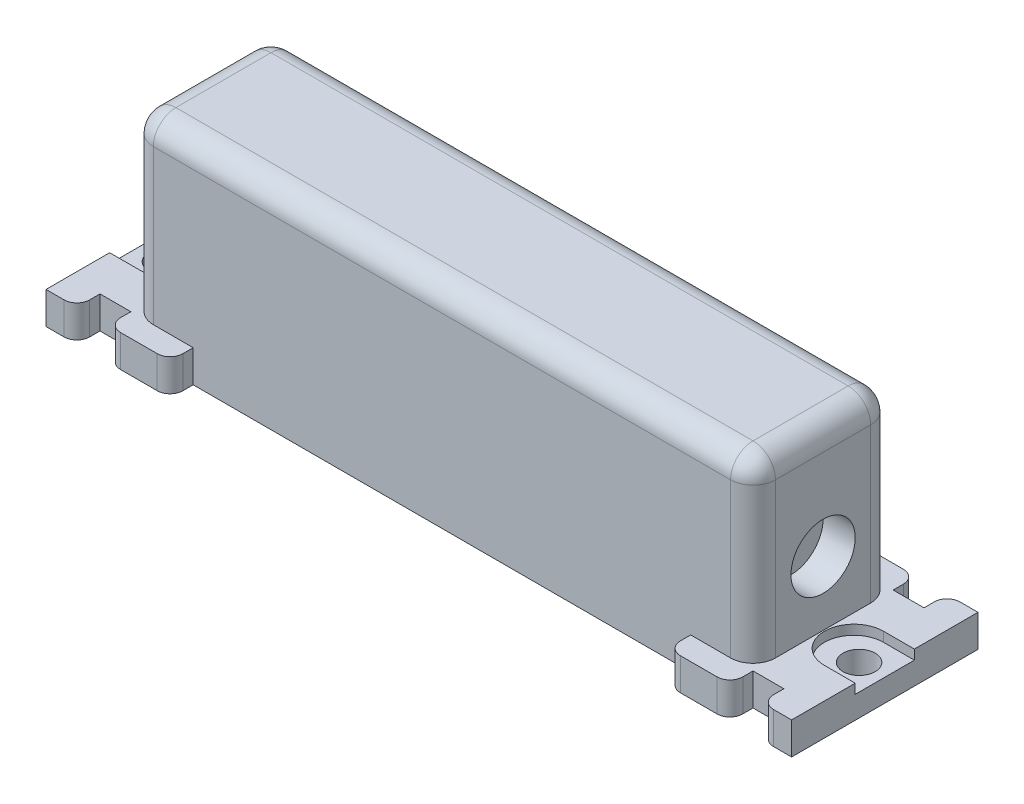
SolidWorks part; units mm, degrees
ref_plane "正面" through (0, 0, 0) normal (0, 0, 1) x (1, 0, 0)
ref_plane "平面" through (0, 0, 0) normal (0, 1, 0) x (1, 0, 0)
ref_plane "右側面" through (0, 0, 0) normal (1, 0, 0) x (0, 0, -1)
sketch "ｽｹｯﾁ1" plane through (0, 0, 0) normal (0, 1, 0) x (1, 0, 0)
  line L0 (-58, -14.5) -> (-58, 14.5)
  line L1 (-58, 14.5) -> (-55.2, 14.5)
  line L2 (-53.2, 12.5) -> (-53.2, 10.9)
  line L3 (-53.2, 10.9) -> (-48.4, 10.9)
  line L4 (-48.4, 10.9) -> (-48.4, 12.5)
  line L5 (57.2676, 0) -> (-76.0537, 0) construction
  line L6 (0, 42.7127) -> (0, -43.6312) construction
  line L7 (-46.4, 14.5) -> (-40.7, 14.5)
  line L8 (-38.7, 12.5) -> (-38.7, 10.9)
  line L9 (-38.7, 10.9) -> (38.7, 10.9)
  line L10 (58, -14.5) -> (58, 14.5)
  line L11 (38.7, 12.5) -> (38.7, 10.9)
  line L12 (46.4, 14.5) -> (40.7, 14.5)
  line L13 (48.4, 10.9) -> (48.4, 12.5)
  line L14 (53.2, 10.9) -> (48.4, 10.9)
  line L15 (53.2, 12.5) -> (53.2, 10.9)
  line L16 (58, 14.5) -> (55.2, 14.5)
  line L17 (58, -14.5) -> (55.2, -14.5)
  line L18 (53.2, -12.5) -> (53.2, -10.9)
  line L19 (53.2, -10.9) -> (48.4, -10.9)
  line L20 (48.4, -10.9) -> (48.4, -12.5)
  line L21 (46.4, -14.5) -> (40.7, -14.5)
  line L22 (38.7, -12.5) -> (38.7, -10.9)
  line L23 (-38.7, -10.9) -> (38.7, -10.9)
  line L24 (-38.7, -12.5) -> (-38.7, -10.9)
  line L25 (-46.4, -14.5) -> (-40.7, -14.5)
  line L26 (-48.4, -10.9) -> (-48.4, -12.5)
  line L27 (-53.2, -10.9) -> (-48.4, -10.9)
  line L28 (-53.2, -12.5) -> (-53.2, -10.9)
  line L29 (-58, -14.5) -> (-55.2, -14.5)
  arc A0 (-55.2, 14.5) -> (-53.2, 12.5) centre (-55.2, 12.5) cw
  arc A1 (-48.4, 12.5) -> (-46.4, 14.5) centre (-46.4, 12.5) cw
  arc A2 (-40.7, 14.5) -> (-38.7, 12.5) centre (-40.7, 12.5) cw
  arc A3 (40.7, 14.5) -> (38.7, 12.5) centre (40.7, 12.5) ccw
  arc A4 (48.4, 12.5) -> (46.4, 14.5) centre (46.4, 12.5) ccw
  arc A5 (55.2, 14.5) -> (53.2, 12.5) centre (55.2, 12.5) ccw
  arc A6 (55.2, -14.5) -> (53.2, -12.5) centre (55.2, -12.5) cw
  arc A7 (48.4, -12.5) -> (46.4, -14.5) centre (46.4, -12.5) cw
  arc A8 (40.7, -14.5) -> (38.7, -12.5) centre (40.7, -12.5) cw
  arc A9 (-40.7, -14.5) -> (-38.7, -12.5) centre (-40.7, -12.5) ccw
  arc A10 (-48.4, -12.5) -> (-46.4, -14.5) centre (-46.4, -12.5) ccw
  arc A11 (-55.2, -14.5) -> (-53.2, -12.5) centre (-55.2, -12.5) ccw
  point P11 (-50.8, 10.9)
  point P25 (0, 10.9)
  point P37 (-58, 0)
  point P62 (0, -10.9)
  point P63 (58, 0)
  dimension "D4" = 9.6
  dimension "D7" = 2
  dimension "D8" = 2
  dimension "D9" = 2
  dimension "D1" = 14.5
  dimension "D2" = 58
  dimension "D3" = 19.3
  dimension "D5" = 4.8
  dimension "D6" = 3.6
extrude "ﾎﾞｽ - 押し出し2" add sketch "ｽｹｯﾁ1" along normal blind 5 contours L9 L11 A3 L12 A4 L13 L14 L15 A5 L16 L10 L17 A6 L18 L19 L20 A7 L21 A8 L22 L23 L24 A9 L25 A10 L26 L27 L28 A11 L29 L0 L1 A0 L2 L3 L4 A1 L7 A2 L8
sketch "ｽｹｯﾁ3" plane through (0, 5, 0) normal (0, 1, 0) x (1, 0, 0)
  line L0 (-38.7, 10.9) -> (38.7, 10.9) construction
  line L1 (-44.9, 10.9) -> (44.9, 10.9)
  line L2 (-48.4, 7.4) -> (-48.4, -7.4)
  line L3 (-44.9, -10.9) -> (44.9, -10.9)
  line L4 (48.4, 7.4) -> (48.4, -7.4)
  line L5 (-38.7, -10.9) -> (38.7, -10.9) construction
  line L6 (48.4, -10.9) -> (48.4, -12.5) construction
  line L7 (-48.4, -10.9) -> (-48.4, -12.5) construction
  arc A0 (44.9, 10.9) -> (48.4, 7.4) centre (44.9, 7.4) cw
  arc A1 (44.9, -10.9) -> (48.4, -7.4) centre (44.9, -7.4) ccw
  arc A2 (-48.4, -7.4) -> (-44.9, -10.9) centre (-44.9, -7.4) ccw
  arc A3 (-44.9, 10.9) -> (-48.4, 7.4) centre (-44.9, 7.4) ccw
  dimension "D1" = 3.5
extrude "ﾎﾞｽ - 押し出し3" add sketch "ｽｹｯﾁ3" along normal blind 27.5
fillet "ﾌｨﾚｯﾄ1" radius 3.5 8 edges at (-47.3749, 32.5, 9.8749) (-48.4, 32.5, 0) (-47.3749, 32.5, -9.8749) (0, 32.5, -10.9) (47.3749, 32.5, -9.8749) (48.4, 32.5, 0) (47.3749, 32.5, 9.8749) (0, 32.5, 10.9)
sketch "ｽｹｯﾁ4" plane through (-48.4, 0, 0) normal (-1, 0, 0) x (0, 0, 1)
  line L0 (0, 5) -> (0, 29) construction
  line L1 (-7.4, 5) -> (7.4, 5) construction
  line L2 (7.4, 29) -> (-7.4, 29) construction
  circle A0 centre (0, 15) radius 5
  dimension "D1" = 10
  dimension "D2" = 10
extrude "ｶｯﾄ - 押し出し1" cut sketch "ｽｹｯﾁ4" against normal blind 5
mirror "ﾐﾗｰ1" about plane through (0, 0, 0) normal (1, 0, 0) of "ｶｯﾄ - 押し出し1"
sketch "ｽｹｯﾁ5" plane through (0, 5, 0) normal (0, 1, 0) x (1, 0, 0)
  line L0 (-58, 0) -> (-39.706, 0) construction
  line L1 (-58, -14.5) -> (-58, 14.5) construction
  line L3 (-53.2, -4.6) -> (-58, -4.6)
  line L4 (-53.2, 10.9) -> (-53.2, -10.9) construction
  line L5 (0, -15.95) -> (0, 15.95) construction
  line L7 (-53.2, 4.6) -> (-58, 4.6)
  line L8 (-58, -4.6) -> (-58, 4.6)
  line L9 (-53.2, -4.6) -> (-58, 4.6) construction
  line L10 (-53.2, 4.6) -> (-58, -4.6) construction
  line L11 (58, 0) -> (39.706, 0) construction
  line L12 (53.2, 4.6) -> (58, -4.6) construction
  line L13 (53.2, -4.6) -> (58, 4.6) construction
  line L14 (58, -4.6) -> (58, 4.6)
  line L15 (53.2, 4.6) -> (58, 4.6)
  line L16 (53.2, -4.6) -> (58, -4.6)
  arc A0 (-53.2, -4.6) -> (-53.2, 4.6) centre (-53.2, 0) ccw
  arc A1 (53.2, -4.6) -> (53.2, 4.6) centre (53.2, 0) cw
  point P5 (-55.6, 0)
  point P25 (55.6, 0)
  dimension "D1" = 4.6
  dimension "4.7" = 4.6
extrude "ｶｯﾄ - 押し出し2" cut sketch "ｽｹｯﾁ5" against normal blind 1.5 and the other way through all
sketch "ｽｹｯﾁ6" plane through (0, 3.5, 0) normal (0, 1, 0) x (1, 0, 0)
  line L0 (-58, 0) -> (-45.7168, 0) construction
  line L1 (-58, 4.6) -> (-58, -4.6) construction
  line L2 (0, -15.95) -> (0, 15.95) construction
  circle A0 centre (-54, 0) radius 2.5
  circle A1 centre (54, 0) radius 2.5
  dimension "D1" = 4
  dimension "D2" = 5
extrude "ｶｯﾄ - 押し出し3" cut sketch "ｽｹｯﾁ6" against normal blind 10
equation "\"51.5.00mm\"=5"
